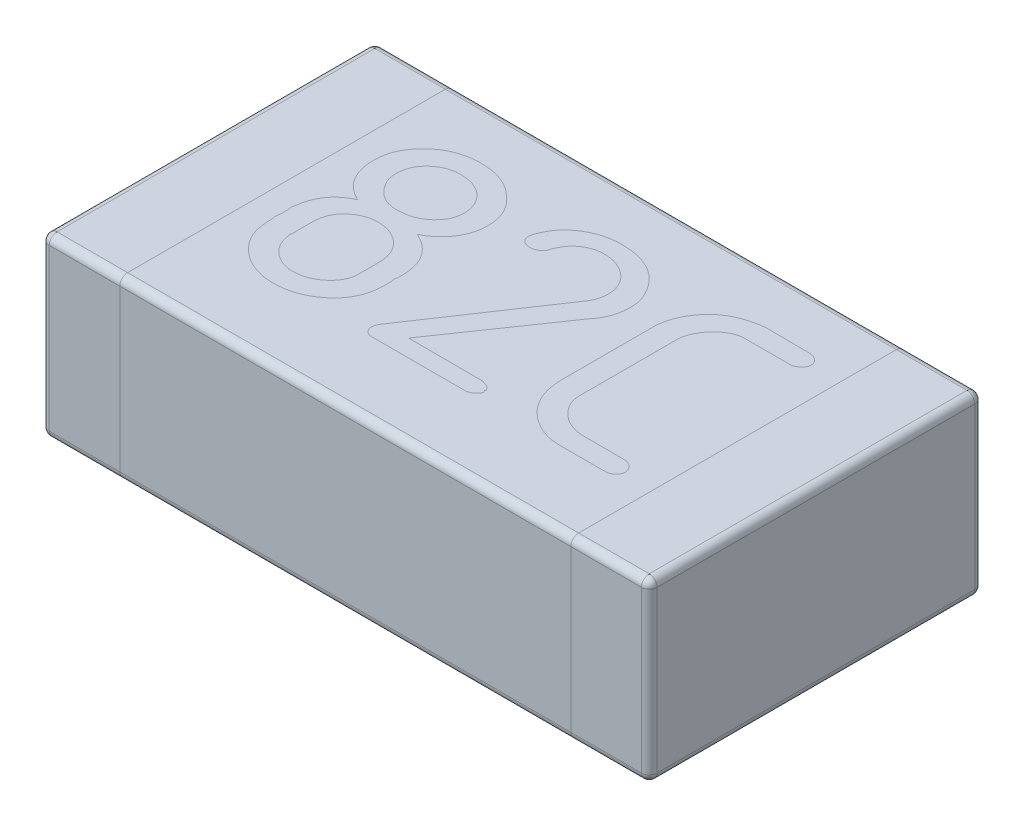
SolidWorks part; units mm, degrees
ref_plane "Front Plane" through (0, 0, 0) normal (0, 0, 1) x (1, 0, 0)
ref_plane "Top Plane" through (0, 0, 0) normal (0, 1, 0) x (1, 0, 0)
ref_plane "Right Plane" through (0, 0, 0) normal (1, 0, 0) x (0, 0, -1)
sketch "Sketch1" plane through (0, 0, 0) normal (0, 1, 0) x (1, 0, 0)
  line L1 (-0.755, -0.425) -> (0.755, -0.425)
  line L2 (-0.775, -0.405) -> (-0.775, 0.405)
  line L3 (-0.755, 0.425) -> (0.755, 0.425)
  line L4 (0.775, -0.405) -> (0.775, 0.405)
  line L5 (-0.775, -0.425) -> (0.775, 0.425) construction
  line L6 (-0.775, 0.425) -> (0.775, -0.425) construction
  arc A4 (-0.775, -0.405) -> (-0.755, -0.425) centre (-0.755, -0.405) ccw
  arc A5 (0.755, -0.425) -> (0.775, -0.405) centre (0.755, -0.405) ccw
  arc A6 (0.775, 0.405) -> (0.755, 0.425) centre (0.755, 0.405) ccw
  arc A7 (-0.755, 0.425) -> (-0.775, 0.405) centre (-0.755, 0.405) ccw
  point P0 (0, 0)
  dimension "D4" = 0.02
  dimension "D1" = 1.55
  dimension "D2" = 0.85
extrude "Boss-Extrude1" add sketch "Sketch1" along normal mid plane 0.45
sketch "Sketch3" plane through (0, 0.225, 0) normal (0, 1, 0) x (1, 0, 0)
  line L0 (-0.575, 0) -> (0.575, 0) construction
  line L1 (-0.575, -0.5133) -> (-0.575, 0.5133)
  line L2 (0.575, -0.5133) -> (0.575, 0.5133)
  line L3 (0, -0.25) -> (0, 0.25) construction
  line L6 (-0.575, -0.25) -> (0.575, -0.25) construction
  text T0 "<b>82C</b>" font "SWIsop1" height 0.53
  point P4 (0, 0)
  point P8 (-0.575, 0)
  point P11 (0.575, 0)
  point P14 (0, 0)
  point P17 (0, -0.25)
  dimension "D1" = 1.15
  dimension "D2" = 0.5
sketch "Sketch4" plane through (0, 0, 0.425) normal (0, 0, 1) x (1, 0, 0)
  line L0 (-0.575, 0.225) -> (-0.575, -0.5946)
  line L1 (0.575, 0.225) -> (0.575, -0.5946)
sketch "Sketch5" plane through (0, 0, -0.425) normal (0, 0, -1) x (-1, 0, 0)
  line L0 (-0.575, 0.225) -> (-0.575, -0.5946) construction
  line L1 (-0.575, 0.225) -> (-0.575, -0.5946)
  line L2 (0.575, 0.225) -> (0.575, -0.5946) construction
  line L3 (0.575, 0.225) -> (0.575, -0.5946)
sketch "Sketch6" plane through (0, -0.225, 0) normal (0, -1, 0) x (1, 0, 0)
  line L0 (0.575, 0.5133) -> (0.575, -0.5133) construction
  line L1 (-0.575, 0.5133) -> (-0.575, -0.5133) construction
  line L2 (0.575, 0.5133) -> (0.575, -0.5133)
  line L3 (-0.575, 0.5133) -> (-0.575, -0.5133)
split line "Split Line2"
split line "Split Line3"
split line "Split Line4"
split line "Split Line5"
fillet "Fillet2" radius 0.02 24 edges at (0.7691, 0.225, 0.4191) (-0.665, -0.225, 0.425) (-0.7691, -0.225, 0.4191) (0, 0.225, 0.425) (-0.665, 0.225, -0.425) (0, 0.225, -0.425) (0.665, 0.225, 0.425) (0.775, 0.225, 0) (0, -0.225, 0.425) (0.665, -0.225, 0.425) (0, -0.225, -0.425) (-0.665, -0.225, -0.425) (0.7691, 0.225, -0.4191) (0.665, 0.225, -0.425) (-0.7691, 0.225, -0.4191) (-0.775, 0.225, 0) (-0.7691, 0.225, 0.4191) (-0.665, 0.225, 0.425) (-0.775, -0.225, 0) (-0.7691, -0.225, -0.4191) (0.665, -0.225, -0.425) (0.7691, -0.225, -0.4191) (0.775, -0.225, 0) (0.7691, -0.225, 0.4191)
